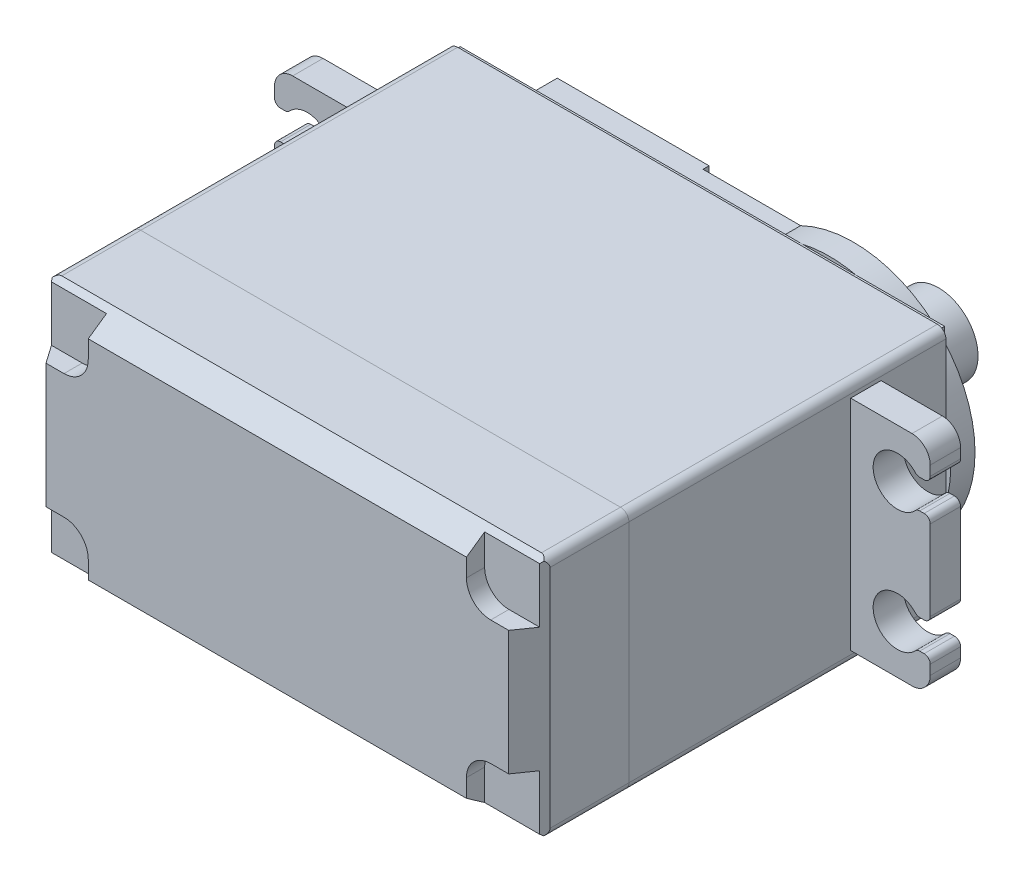
SolidWorks part; units mm, degrees
ref_plane "Front Plane" through (0, 0, 0) normal (0, 0, 1) x (1, 0, 0)
ref_plane "Top Plane" through (0, 0, 0) normal (0, 1, 0) x (1, 0, 0)
ref_plane "Right Plane" through (0, 0, 0) normal (1, 0, 0) x (0, 0, -1)
sketch "Sketch1" plane through (0, 0, 0) normal (0, 0, 1) x (1, 0, 0)
  line L1 (-20.45, -10) -> (20.45, -10)
  line L2 (-20.45, -10) -> (-20.45, 10)
  line L3 (-20.45, 10) -> (20.45, 10)
  line L4 (20.45, -10) -> (20.45, 10)
  line L5 (-20.45, -10) -> (20.45, 10) construction
  line L6 (-20.45, 10) -> (20.45, -10) construction
  point P0 (0, 0)
  dimension "D1" = 20
  dimension "D2" = 40.9
extrude "Boss-Extrude3" add sketch "Sketch1" along normal blind 19.3
sketch "Sketch4" plane through (0, 0, 0) normal (0, 0, -1) x (-1, 0, 0)
  line L4 (-20.45, 10) -> (-20.45, -10)
  line L5 (-20.45, -10) -> (20.45, -10)
  line L6 (20.45, -10) -> (20.45, 10)
  line L7 (20.45, 10) -> (-20.45, 10)
  line L8 (-20.45, 10) -> (-20.45, -10)
  line L9 (-20.45, -10) -> (20.45, -10)
  line L10 (20.45, -10) -> (20.45, 10)
  line L11 (20.45, 10) -> (-20.45, 10)
  dimension "D1" = 0
extrude "Boss-Extrude4" add sketch "Sketch4" along normal blind 6.8 separate body
sketch "Sketch5" plane through (0, 0, -6.8) normal (0, 0, -1) x (-1, 0, 0)
  line L4 (20.45, 10) -> (-20.45, 10)
  line L5 (-20.45, 10) -> (-20.45, -10)
  line L6 (-20.45, -10) -> (20.45, -10)
  line L7 (20.45, -10) -> (20.45, 10)
  line L8 (20.45, 10) -> (-20.45, 10)
  line L9 (-20.45, 10) -> (-20.45, -10)
  line L10 (-20.45, -10) -> (20.45, -10)
  line L11 (20.45, -10) -> (20.45, 10)
  point P2 (0, 0)
  dimension "D1" = 0
sketch "Sketch6" plane through (0, 0, 19.3) normal (0, 0, 1) x (1, 0, 0)
  line L4 (20.45, -10) -> (20.45, 10)
  line L5 (20.45, 10) -> (-20.45, 10)
  line L6 (-20.45, 10) -> (-20.45, -10)
  line L7 (-20.45, -10) -> (20.45, -10)
  line L8 (20.45, -10) -> (20.45, 10)
  line L9 (20.45, 10) -> (-20.45, 10)
  line L10 (-20.45, 10) -> (-20.45, -10)
  line L11 (-20.45, -10) -> (20.45, -10)
  dimension "D1" = 0
extrude "Boss-Extrude6" add sketch "Sketch6" along normal blind 8.5 separate body
chamfer "Chamfer1" distance 2 angle 35 4 edges at (-20.45, 0, 27.8) (0, 10, 27.8) (20.45, 0, 27.8) (0, -10, 27.8)
sketch "Sketch7" plane through (0, 0, 27.8) normal (0, 0, 1) x (1, 0, 0)
  line L0 (0, 0) -> (0, 10) construction
  line L1 (-20.45, 10) -> (-15.57, 10)
  line L2 (-20.45, 10) -> (-20.45, 5.12)
  line L3 (-20.45, 5.12) -> (-17.57, 5.12)
  line L4 (-15.57, 10) -> (-15.57, 7.12)
  line L5 (-20.45, 10) -> (20.45, 10) construction
  line L6 (0, 0) -> (20.45, 0) construction
  line L7 (20.45, 10) -> (20.45, -10) construction
  line L8 (20.45, 5.12) -> (17.57, 5.12)
  line L9 (15.57, 10) -> (15.57, 7.12)
  line L10 (20.45, 10) -> (15.57, 10)
  line L11 (20.45, 10) -> (20.45, 5.12)
  line L12 (20.45, -10) -> (20.45, -5.12)
  line L13 (20.45, -10) -> (15.57, -10)
  line L14 (15.57, -10) -> (15.57, -7.12)
  line L15 (20.45, -5.12) -> (17.57, -5.12)
  line L16 (-15.57, -10) -> (-15.57, -7.12)
  line L17 (-20.45, -5.12) -> (-17.57, -5.12)
  line L18 (-20.45, -10) -> (-20.45, -5.12)
  line L19 (-20.45, -10) -> (-15.57, -10)
  arc A0 (-17.57, 5.12) -> (-15.57, 7.12) centre (-17.57, 7.12) ccw
  arc A1 (17.57, 5.12) -> (15.57, 7.12) centre (17.57, 7.12) cw
  arc A2 (17.57, -5.12) -> (15.57, -7.12) centre (17.57, -7.12) ccw
  arc A3 (-17.57, -5.12) -> (-15.57, -7.12) centre (-17.57, -7.12) cw
  dimension "D3" = 2
  dimension "D1" = 4.88
  dimension "D2" = 4.88
extrude "Cut-Extrude1" cut sketch "Sketch7" against normal blind 1.5
sketch "Sketch8" plane through (0, 0, -6.8) normal (0, 0, -1) x (-1, 0, 0)
  line L0 (20.45, 10) -> (-20.45, 10) construction
  line L1 (19.95, -9.75) -> (-19.95, -9.75)
  line L2 (19.95, -9.75) -> (19.95, 9.75)
  line L3 (19.95, 9.75) -> (-19.95, 9.75)
  line L4 (-19.95, -9.75) -> (-19.95, 9.75)
  line L5 (19.95, -9.75) -> (-19.95, 9.75) construction
  line L6 (19.95, 9.75) -> (-19.95, -9.75) construction
  line L7 (20.45, -10) -> (20.45, 10) construction
  point P0 (0, 0)
  dimension "D1" = 0.25
  dimension "D2" = 0.5
extrude "Boss-Extrude7" add sketch "Sketch8" along normal blind 0.4
sketch "Sketch9" plane through (0, 0, -7.2) normal (0, 0, -1) x (-1, 0, 0)
  line L0 (-20.45, 0) -> (20.45, 0) construction
  line L1 (-20.45, 10) -> (-20.45, -10) construction
  line L2 (20.45, -10) -> (20.45, 10) construction
  line L3 (20.45, 10) -> (-20.45, 10) construction
  line L4 (-6.09, 10) -> (-6.09, -10) construction
  line L5 (-20.45, -10) -> (20.45, -10) construction
  line L6 (-6.09, 8.9995) -> (14.45, 8.9995)
  line L7 (14.45, 8.9995) -> (14.45, 3)
  line L8 (14.45, -8.9995) -> (14.45, -3)
  line L9 (-6.09, -8.9995) -> (14.45, -8.9995)
  arc A0 (-6.09, 8.9995) -> (-6.09, -8.9995) centre (-10.45, 0) ccw
  arc A1 (14.45, -3) -> (14.45, 3) centre (14.45, 0) ccw
  point P19 (14.508, 3.4687)
  point P21 (17.45, 0)
  dimension "D1" = 14.36
  dimension "D2" = 6
  dimension "D3" = 3
extrude "Boss-Extrude8" add sketch "Sketch9" along normal blind 2
sketch "Sketch10" plane through (0, 0, -9.2) normal (0, 0, -1) x (-1, 0, 0)
  circle A0 centre (-10.45, 0) radius 6.5
  dimension "D1" = 13
extrude "Boss-Extrude9" add sketch "Sketch10" along normal blind 1.5
sketch "Sketch11" plane through (0, 0, -10.7) normal (0, 0, -1) x (-1, 0, 0)
  circle A0 centre (-10.45, 0) radius 5.5
  dimension "D1" = 11
extrude "Boss-Extrude10" add sketch "Sketch11" along normal blind 0.5
sketch "Sketch12" plane through (0, 0, -11.2) normal (0, 0, -1) x (-1, 0, 0)
  circle A0 centre (-10.45, 0) radius 3.25
  dimension "D1" = 6.5
extrude "Boss-Extrude11" add sketch "Sketch12" along normal blind 5
sketch "Sketch13" plane through (0, 0, -9.2) normal (0, 0, -1) x (-1, 0, 0)
  line L0 (-6.09, -8.9995) -> (14.45, -8.9995) construction
  line L1 (14.45, 8.9995) -> (1.95, 8.9995)
  line L2 (14.45, 8.9995) -> (14.45, -8.9995)
  line L3 (14.45, -8.9995) -> (1.95, -8.9995)
  line L4 (1.95, 8.9995) -> (1.95, 1.75)
  line L5 (13.45, 7.9995) -> (2.95, 7.9995)
  line L6 (2.95, 7.9995) -> (2.95, -7.9995)
  line L7 (13.45, -7.9995) -> (2.95, -7.9995)
  line L8 (13.45, 7.9995) -> (13.45, -7.9995)
  line L9 (1.95, -1.75) -> (1.95, -8.9995)
  line L11 (1.95, 8.9995) -> (1.95, -8.9995) construction
  arc A0 (1.95, 1.75) -> (1.95, -1.75) centre (1.95, 0) ccw
  dimension "D3" = 3.5
  dimension "D1" = 12.5
  dimension "D2" = 1
extrude "Boss-Extrude12" add sketch "Sketch13" along normal blind 0.5
fillet "Fillet1" radius 0.7 4 edges at (-20.45, -10, 9.65) (-20.45, 10, 9.65) (20.45, 10, 9.65) (20.45, -10, 9.65)
fillet "Fillet6" radius 0.7 4 edges at (-20.45, 10, -3.4) (-20.45, -10, -3.4) (20.45, 10, -3.4) (20.45, -10, -3.4)
fillet "Fillet7" radius 0.7 4 edges at (-20.45, -10, 22.55) (20.45, -10, 22.55) (-20.45, 10, 22.55) (20.45, 10, 22.55)
sketch "Sketch16" plane through (0, 0, -7.2) normal (0, 0, -1) x (-1, 0, 0)
  line L0 (20.45, 9) -> (25.5, 9)
  line L1 (20.45, -10) -> (20.45, 10) construction
  line L2 (0.2, 0) -> (27, 0) construction
  line L3 (27, 7.5) -> (27, 6.7)
  line L4 (20.45, 10) -> (-20.45, 10) construction
  line L5 (0, 10) -> (0, -8.9995) construction
  line L6 (-6.09, -8.9995) -> (1.95, -8.9995) construction
  line L7 (25.9, 9) -> (25.9, -9) construction
  line L8 (26.133, 6.2) -> (26.5, 6.2)
  line L9 (26.133, 3.8) -> (26.5, 3.8)
  line L10 (27, 3.3) -> (27, -3.3)
  line L11 (26.133, -3.8) -> (26.5, -3.8)
  line L12 (26.133, -6.2) -> (26.5, -6.2)
  line L13 (27, -7.5) -> (27, -6.7)
  line L14 (20.45, -9) -> (25.5, -9)
  line L15 (20.45, 9) -> (20.45, -9)
  arc A0 (1.95, 1.75) -> (1.95, -1.75) centre (1.95, 0) ccw construction
  arc A1 (25.7664, 6.36) -> (25.7664, 3.64) centre (24.3, 5) ccw
  arc A2 (25.7664, 3.64) -> (26.133, 3.8) centre (26.133, 3.3) cw
  arc A3 (25.7664, 6.36) -> (26.133, 6.2) centre (26.133, 6.7) ccw
  arc A4 (26.5, 3.8) -> (27, 3.3) centre (26.5, 3.3) cw
  arc A5 (26.5, 6.2) -> (27, 6.7) centre (26.5, 6.7) ccw
  arc A6 (25.5, 9) -> (27, 7.5) centre (25.5, 7.5) cw
  arc A7 (25.5, -9) -> (27, -7.5) centre (25.5, -7.5) ccw
  arc A8 (26.5, -6.2) -> (27, -6.7) centre (26.5, -6.7) cw
  arc A9 (26.5, -3.8) -> (27, -3.3) centre (26.5, -3.3) ccw
  arc A10 (25.7664, -6.36) -> (26.133, -6.2) centre (26.133, -6.7) cw
  arc A11 (25.7664, -3.64) -> (26.133, -3.8) centre (26.133, -3.3) ccw
  arc A12 (25.7664, -6.36) -> (25.7664, -3.64) centre (24.3, -5) cw
  point P26 (25.9, 3.8)
  point P29 (25.9, 6.2)
  point P32 (27, 3.8)
  point P38 (25.9, 0)
  point P55 (27, -3.8)
  point P56 (25.9, -6.2)
  point P57 (25.9, -3.8)
  dimension "D3" = 4
  dimension "D7" = 0.5
  dimension "D8" = 1.5
  dimension "D1" = 6.55
  dimension "D2" = 1
  dimension "D4" = 5
  dimension "D5" = 24.3
  dimension "D6" = 1.1
extrude "Boss-Extrude13" add sketch "Sketch16" against normal blind 2.5 from offset 5.74 offset against normal yes
mirror "Mirror1" about plane through (0, 0, 0) normal (1, 0, 0) of "Boss-Extrude13"
